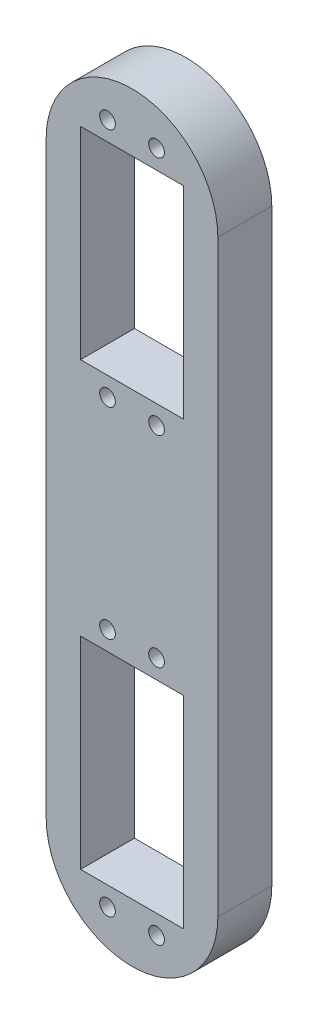
SolidWorks part; units mm, degrees
ref_plane "Front Plane" through (0, 0, 0) normal (0, 0, 1) x (1, 0, 0)
ref_plane "Top Plane" through (0, 0, 0) normal (0, 1, 0) x (1, 0, 0)
ref_plane "Right Plane" through (0, 0, 0) normal (1, 0, 0) x (0, 0, -1)
sketch "Sketch1" plane through (0, 0, 0) normal (0, 0, 1) x (1, 0, 0)
  line L0 (-20, 10) -> (15, 10) construction
  line L2 (-20, 70) -> (-20, -50)
  line L4 (15, 70) -> (15, -50)
  line L5 (-13, 75.5) -> (8, 75.5)
  line L6 (-13, 75.5) -> (-13, 34.5)
  line L7 (-13, 34.5) -> (8, 34.5)
  line L8 (8, 75.5) -> (8, 34.5)
  line L9 (-2.5, 75.5) -> (-2.5, 79.5) construction
  line L10 (-2.5, 79.5) -> (-7.5, 79.5) construction
  line L11 (-2.5, 79.5) -> (2.5, 79.5) construction
  line L12 (-13, 55) -> (8, 55) construction
  line L13 (-7.5, 79.5) -> (-7.5, 30.5) construction
  arc A3 (15, 70) -> (-20, 70) centre (-2.5, 70) ccw
  arc A4 (-20, -50) -> (15, -50) centre (-2.5, -50) ccw
  circle A5 centre (-7.5, 79.5) radius 1.6
  circle A6 centre (2.5, 79.5) radius 1.6
  circle A7 centre (2.5, 30.5) radius 1.6
  circle A8 centre (-7.5, 30.5) radius 1.6
  point P0 (0, 0)
  point P7 (-2.5, 87.5)
  dimension "D4" = 41
  dimension "D5" = 21
  dimension "D7" = 12
  dimension "D11" = 3.2
  dimension "D1" = 120
  dimension "D2" = 35
  dimension "D3" = 120
  dimension "D6" = 7
  dimension "D8" = 4
  dimension "D10" = 5
sketch "Sketch2" plane through (0, 0, 0) normal (0, 0, 1) x (1, 0, 0)
sketch "Sketch3" plane through (0, 0, 0) normal (0, 0, 1) x (1, 0, 0)
extrude "Boss-Extrude1" add sketch "Sketch1" along normal blind 11
sketch "Sketch6" plane through (0, 0, 11) normal (0, 0, 1) x (1, 0, 0)
  line L0 (8, 34.5) -> (8, 75.5) construction
  line L1 (-13, 34.5) -> (8, 34.5) construction
  line L2 (15, -50) -> (15, 70)
  line L3 (-20, 70) -> (-20, -50)
  line L4 (15, -50) -> (15, 70)
  line L5 (-20, 70) -> (-20, -50)
  line L6 (8, 75.5) -> (-13, 75.5) construction
  line L7 (-13, 75.5) -> (-13, 34.5) construction
  line L8 (8, 34.5) -> (8, 75.5)
  line L9 (-13, 34.5) -> (8, 34.5)
  line L10 (8, 75.5) -> (-13, 75.5)
  line L11 (-13, 75.5) -> (-13, 34.5)
  line L12 (-13, 34.5) -> (8, 34.5)
  line L13 (-13, 75.6) -> (8, 75.6)
  line L14 (-13, 75.6) -> (-13, 34.4)
  line L15 (-13, 34.4) -> (8, 34.4)
  line L16 (8, 75.6) -> (8, 34.4)
  line L17 (-13, 75.5) -> (8, 75.5)
  arc A2 (-20, -50) -> (15, -50) centre (-2.5, -50) ccw
  arc A3 (15, 70) -> (-20, 70) centre (-2.5, 70) ccw
  arc A4 (-20, -50) -> (15, -50) centre (-2.5, -50) ccw
  arc A5 (15, 70) -> (-20, 70) centre (-2.5, 70) ccw
  line M15 (8, 34.5) -> (-13, 34.5)
  line M17 (-13, 75.5) -> (8, 75.5)
  dimension "D2" = 0.1
  dimension "D3" = 0.1
  dimension "D1" = 0
extrude "Cut-Extrude1" cut sketch "Sketch6" against normal through all contours L16 L13 L14 M17 | L16 L14 L15 M15
sketch "Sketch7" plane through (0, 0, 0) normal (0, 0, -1) x (-1, 0, 0)
  line L0 (13, 34.4) -> (-8, 34.4) construction
  line L1 (13, 75.6) -> (13, 34.4) construction
  line L2 (13, 75.6) -> (-8, 75.6) construction
  line L3 (-8, 34.4) -> (-8, 75.6) construction
  line L4 (13, 34.4) -> (-8, 34.4)
  line L5 (13, 75.6) -> (13, 34.4)
  line L6 (13, 75.6) -> (-8, 75.6)
  line L7 (-8, 34.4) -> (-8, 75.6)
  line L8 (-15, 10) -> (20, 10) construction
  line L9 (-15, -50) -> (-15, 70) construction
  line L10 (20, 70) -> (20, -50) construction
  line L11 (13, -55.6) -> (13, -14.4)
  line L12 (13, -55.6) -> (-8, -55.6)
  line L13 (-8, -14.4) -> (-8, -55.6)
  line L14 (13, -14.4) -> (-8, -14.4)
  circle A0 centre (7.5, 79.5) radius 1.6 construction
  circle A1 centre (-2.5, 79.5) radius 1.6 construction
  circle A2 centre (7.5, 30.5) radius 1.6 construction
  circle A3 centre (-2.5, 30.5) radius 1.6 construction
  circle A4 centre (7.5, 79.5) radius 1.6
  circle A5 centre (-2.5, 79.5) radius 1.6
  circle A6 centre (7.5, 30.5) radius 1.6
  circle A7 centre (-2.5, 30.5) radius 1.6
  circle A8 centre (7.5, -10.5) radius 1.6
  circle A9 centre (-2.5, -10.5) radius 1.6
  circle A10 centre (-2.5, -59.5) radius 1.6
  circle A11 centre (7.5, -59.5) radius 1.6
extrude "Cut-Extrude2" cut sketch "Sketch7" against normal up to surface (11 mm away) contours L11 L14 L13 L12 | A9 | A8 | A10 | A11 up to face at (4.1, 30.5, 11)
